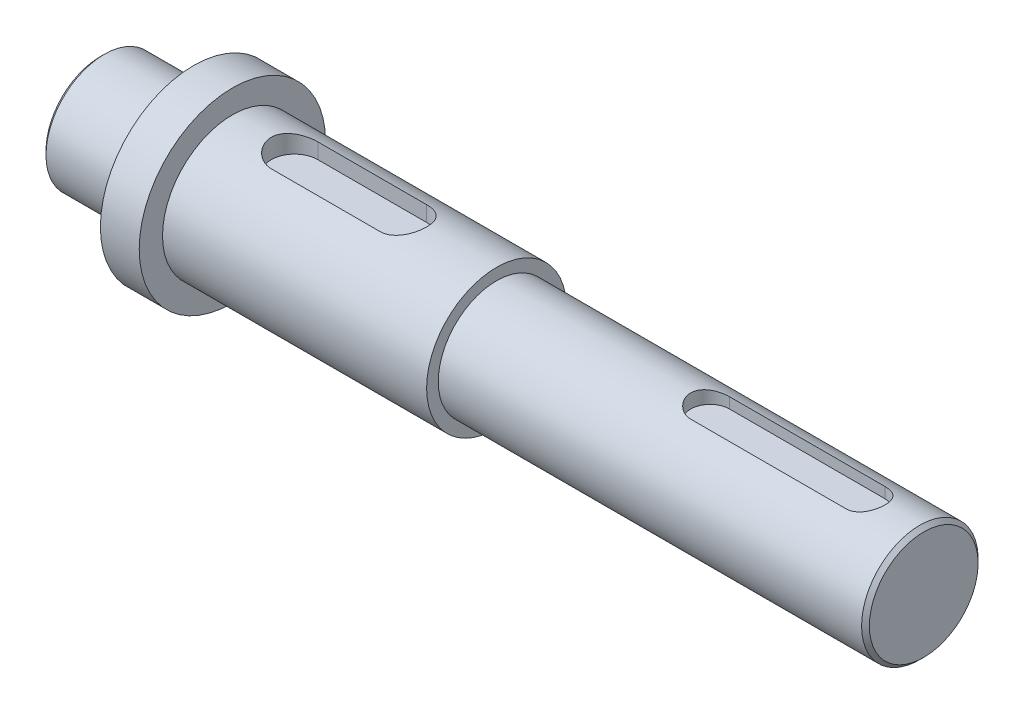
SolidWorks part; units mm, degrees
ref_plane "Front Plane" through (0, 0, 0) normal (0, 0, 1) x (1, 0, 0)
ref_plane "Top Plane" through (0, 0, 0) normal (0, 1, 0) x (1, 0, 0)
ref_plane "Right Plane" through (0, 0, 0) normal (1, 0, 0) x (0, 0, -1)
sketch "Sketch1" plane through (0, 0, 0) normal (0, 0, 1) x (1, 0, 0)
  line L0 (-89.7078, 0) -> (116.6603, 0) construction
  line L1 (-69.1917, 0) -> (-69.1917, 7.5)
  line L2 (-69.1917, 7.5) -> (-57.1917, 7.5)
  line L3 (-57.1917, 7.5) -> (-57.1917, 12)
  line L4 (-57.1917, 12) -> (-52.1917, 12)
  line L5 (-52.1917, 12) -> (-52.1917, 9)
  line L6 (-52.1917, 9) -> (-18.1917, 9)
  line L7 (-18.1917, 9) -> (-18.1917, 7.5)
  line L8 (-18.1917, 7.5) -> (36.8083, 7.5)
  line L9 (36.8083, 7.5) -> (36.8083, 0)
  line L10 (-69.1917, 0) -> (36.8083, 0)
  dimension "D1" = 106
  dimension "D2" = 55
  dimension "D3" = 5
  dimension "D4" = 34
  dimension "D5" = 18
  dimension "D6" = 15
  dimension "D7" = 7.5
  dimension "D8" = 24
revolve "Revolve1" add sketch "Sketch1" angle 360 about L0
ref_plane "Plane1" through (0, 9, 0) normal (0, 1, 0) x (1, 0, 0)
sketch "Sketch2" plane through (0, 9, 0) normal (0, 1, 0) x (1, 0, 0)
  line L0 (-44.1917, 0) -> (-30.1917, 0) construction
  line L1 (-44.1917, 3) -> (-30.1917, 3)
  line L2 (-44.1917, -3) -> (-30.1917, -3)
  line L3 (-52.1917, -9) -> (-52.1917, 9) construction
  arc A0 (-44.1917, 3) -> (-44.1917, -3) centre (-44.1917, 0) ccw
  arc A1 (-30.1917, -3) -> (-30.1917, 3) centre (-30.1917, 0) ccw
  point P3 (-37.1917, 0)
  dimension "D3" = 3
  dimension "D4" = 6
  dimension "D1" = 14
  dimension "D2" = 8
extrude "Cut-Extrude1" cut sketch "Sketch2" against normal blind 2.5
ref_plane "Plane2" through (0, 7.5, 0) normal (0, 1, 0) x (1, 0, 0)
sketch "Sketch3" plane through (0, 7.5, 0) normal (0, 1, 0) x (1, 0, 0)
  line L0 (9.3083, 0) -> (29.3083, 0) construction
  line L1 (9.3083, 2.5) -> (29.3083, 2.5)
  line L2 (9.3083, -2.5) -> (29.3083, -2.5)
  line L3 (36.8083, -7.5) -> (36.8083, 7.5) construction
  arc A0 (9.3083, 2.5) -> (9.3083, -2.5) centre (9.3083, 0) ccw
  arc A1 (29.3083, -2.5) -> (29.3083, 2.5) centre (29.3083, 0) ccw
  point P3 (19.3083, 0)
  dimension "D1" = 20
  dimension "D2" = 5
  dimension "D3" = 7.5
extrude "Cut-Extrude2" cut sketch "Sketch3" against normal blind 1.8
chamfer "Chamfer1" distance 0.5 angle 45 2 edges at (36.8083, 0, 7.5) (-69.1917, 0, 7.5)
